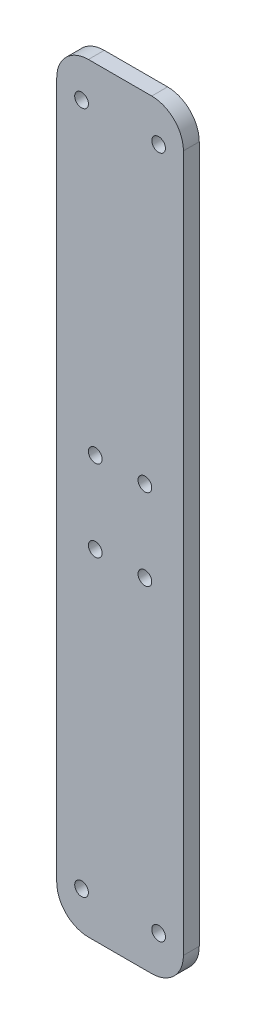
SolidWorks part; units mm, degrees
ref_plane "Front Plane" through (0, 0, 0) normal (0, 0, 1) x (1, 0, 0)
ref_plane "Top Plane" through (0, 0, 0) normal (0, 1, 0) x (1, 0, 0)
ref_plane "Right Plane" through (0, 0, 0) normal (1, 0, 0) x (0, 0, -1)
sketch "Sketch1" plane through (0, 0, 8) normal (0, 0, 1) x (1, 0, 0)
  line L0 (273.05, -152.4) -> (-273.05, -152.4) construction
  line L1 (-31.75, -152.4) -> (-82.55, -152.4)
  line L2 (-31.75, -152.4) -> (-31.75, 152.4)
  line L3 (-31.75, 152.4) -> (-82.55, 152.4)
  line L4 (-82.55, -152.4) -> (-82.55, 152.4)
  line L5 (-31.75, -152.4) -> (-82.55, 152.4)
  line L6 (-31.75, 152.4) -> (-82.55, -152.4)
  line L7 (-69.85, -136.95) -> (-72.6, -136.95) construction
  line L8 (-31.75, -150.9) -> (-31.75, -134.85) construction
  line L9 (-57.15, 0) -> (-82.55, 0)
  line L10 (-49.53, 139.7) -> (-64.77, 139.7)
  line L11 (-49.53, 139.7) -> (-49.53, -139.7)
  line L12 (-49.53, -139.7) -> (-64.77, -139.7)
  line L13 (-64.77, 139.7) -> (-64.77, -139.7)
  line L14 (-49.53, 139.7) -> (-64.77, -139.7)
  line L15 (-49.53, -139.7) -> (-64.77, 139.7)
  line L16 (-72.6, -136.95) -> (-72.6, -139.7) construction
  line L17 (-44.45, -139.7) -> (-44.45, -136.95) construction
  line L18 (-41.7, 136.95) -> (-41.7, 139.7) construction
  circle A0 centre (-69.85, -139.7) radius 12.7
  circle A1 centre (-44.45, -139.7) radius 12.7
  circle A2 centre (-44.45, -139.7) radius 2.75
  circle A3 centre (-69.85, -139.7) radius 2.75
  circle A4 centre (-273.05, -139.7) radius 2.75 construction
  circle A5 centre (-44.45, 139.7) radius 2.75
  circle A6 centre (-69.85, 139.7) radius 2.75
  circle A7 centre (-69.85, 139.7) radius 12.7
  circle A8 centre (-44.45, 139.7) radius 12.7
  circle A9 centre (-72.6, -136.95) radius 2.75
  circle A10 centre (-41.7, -136.95) radius 2.75
  circle A11 centre (-72.6, 136.95) radius 2.75
  circle A12 centre (-72.6, 136.95) radius 2.75
  circle A14 centre (-41.7, 136.95) radius 2.75
  point P4 (-57.15, 0)
  point P28 (-57.15, 0)
  line M50 (-31.75, 139.7) -> (-260.35, 139.7)
  line M54 (-260.35, -139.7) -> (-31.75, -139.7)
  dimension "D1" = 304.8
  dimension "D2" = 15.24
extrude "Boss-Extrude3" add sketch "Sketch1" against normal blind 6.35 contours L6 A8 L2 A1 L5 L11 | L6 A0 L4 L9 L13 | L5 A1 L11 | L13 A0 L6 | A3 A0 L6 M54 | A0 A1 L1 | A2 L5 A1 L12 M54 | A2 A10 L11 A1 L5 M54 | A0 L6 M54 | A1 L5 M54 | A1 L5 M54 | A0 L6 M54 | L4 A7 L5 L13 L9 | L11 A8 L6 | L5 A7 L13 | A7 L10 A6 L5 M50 | A6 A11 L13 A7 L5 M50 | A8 L6 A5 M50 | A5 A12 L6 A8 L11 M50 | A8 L6 M50 | A8 L6 M50 | A7 L5 M50 | A7 L5 M50 | A6 M50 | A5 M50 | A11 A6 M50 | A6 A11 M50 | A12 A5 M50 | A5 A12 M50 | L3 A8 A7 | A3 M54 | A3 A9 L6 A0 L13 M54 | A9 A3 M54 | A3 A9 M54 | A2 M54 | A2 A10 M54 | A10 A2 M54
sketch "Sketch2" plane through (0, 0, 8) normal (0, 0, 1) x (1, 0, 0)
  circle A0 centre (-41.7, 136.95) radius 2.75
  circle A1 centre (-72.6, 136.95) radius 2.75
  circle A2 centre (-41.7, -136.95) radius 2.75
  circle A3 centre (-72.6, -136.95) radius 2.75
  arc A4 (-69.85, -136.95) -> (-72.6, -139.7) centre (-72.6, -136.95) ccw construction
  arc A5 (-72.6, 139.7) -> (-69.85, 136.95) centre (-72.6, 136.95) ccw construction
extrude "Cut-Extrude1" cut sketch "Sketch2" against normal through all
sketch "Sketch3" plane through (0, 0, 8) normal (0, 0, 1) x (1, 0, 0)
  line L1 (-64.77, 139.7) -> (-49.53, 139.7)
  line L2 (-64.77, 139.7) -> (-64.77, -139.7)
  line L3 (-64.77, -139.7) -> (-49.53, -139.7)
  line L4 (-49.53, 139.7) -> (-49.53, -139.7)
  line L5 (-64.77, 139.7) -> (-49.53, -139.7) construction
  line L6 (-64.77, -139.7) -> (-49.53, 139.7) construction
  point P4 (-57.15, 0)
extrude "Boss-Extrude4" add sketch "Sketch3" against normal up to surface (6.35 mm away) up to face at (-75.35, 136.95, 1.65)
sketch "Sketch4" plane through (0, 0, 1.65) normal (0, 0, -1) x (-1, 0, 0)
  line L0 (31.75, -139.7) -> (31.75, 139.7) construction
  line L1 (31.75, 6.35) -> (82.55, 6.35) construction
  line L2 (31.75, 6.35) -> (31.75, -6.35)
  line L3 (31.75, -6.35) -> (82.55, -6.35) construction
  line L4 (82.55, 6.35) -> (82.55, -6.35)
  line L5 (82.55, -139.7) -> (82.55, 139.7) construction
  line L6 (44.45, -136.95) -> (44.45, -16.3) construction
  line L7 (69.85, -136.95) -> (69.85, -16.3) construction
  line L8 (47.2, -16.3) -> (67.1, -16.3) construction
  line L9 (47.2, -16.3) -> (47.2, 16.3) construction
  line L10 (47.2, 16.3) -> (67.1, 16.3) construction
  line L11 (67.1, -16.3) -> (67.1, 16.3) construction
  line L12 (47.2, 16.3) -> (57.15, 6.35) construction
  line L13 (57.15, 6.35) -> (67.1, 16.3) construction
  circle A0 centre (47.2, 16.3) radius 2.75
  circle A1 centre (67.1, 16.3) radius 2.75
  circle A2 centre (47.2, -16.3) radius 2.75
  circle A3 centre (67.1, -16.3) radius 2.75
  circle A4 centre (41.7, -136.95) radius 2.75 construction
  circle A5 centre (72.6, -136.95) radius 2.75 construction
  point P14 (42.0644, -18.6016)
  point P16 (31.75, 0)
  point P17 (31.75, 0)
  point P18 (47.2, 0)
  point P28 (57.15, -16.3)
  dimension "D1" = 12.7
extrude "Cut-Extrude2" cut sketch "Sketch4" against normal through all both and the other way through all contours A2 | A3 | A1 | A0
